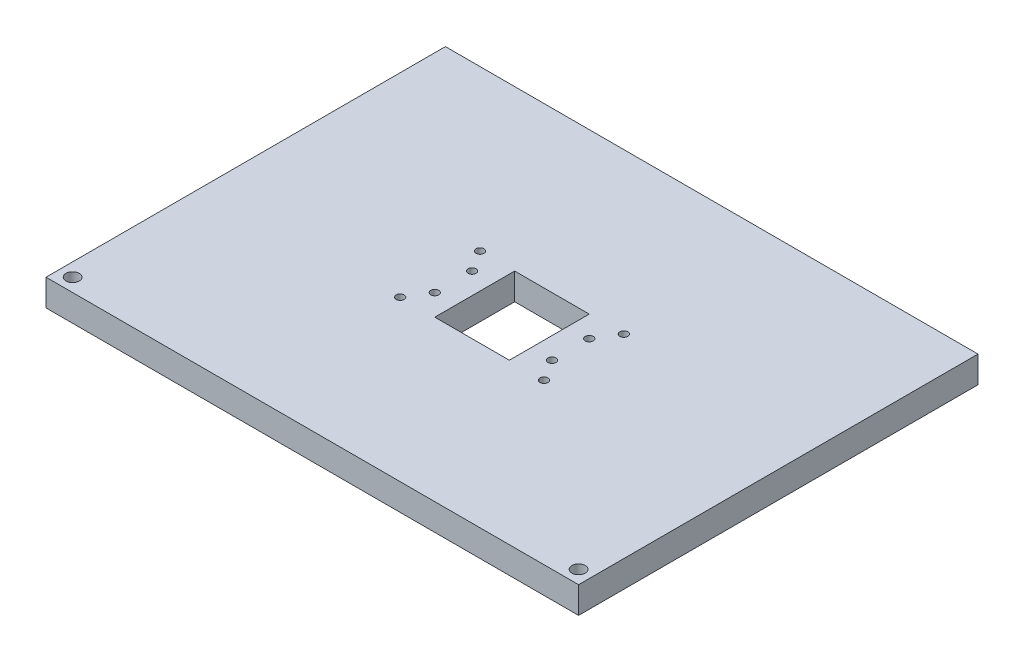
SolidWorks part; units mm, degrees
material "Perspex (TM) GS Acrylic Cast Sheet"
ref_plane "Front Plane" through (0, 0, 0) normal (0, 0, 1) x (1, 0, 0)
ref_plane "Top Plane" through (0, 0, 0) normal (0, 1, 0) x (1, 0, 0)
ref_plane "Right Plane" through (0, 0, 0) normal (1, 0, 0) x (0, 0, -1)
sketch "Sketch1" plane through (0, 0, 0) normal (0, 0, 1) x (1, 0, 0)
  line L1 (-100, 30) -> (100, 30)
  line L2 (-100, 30) -> (-100, -30)
  line L3 (-100, -30) -> (100, -30)
  line L4 (100, 30) -> (100, -30)
  line L5 (-100, 30) -> (100, -30) construction
  line L6 (-100, -30) -> (100, 30) construction
  point P0 (0, 0)
  dimension "D1" = 200
  dimension "D2" = 60
extrude "Boss-Extrude1" add sketch "Sketch1" along normal blind 10
sketch "Sketch2" plane through (0, 0, 0) normal (0, 0, -1) x (-1, 0, 0)
  line L0 (-100, -30) -> (-100, -20)
  line L1 (-100, -30) -> (-100, 30) construction
  line L2 (-100, -20) -> (100, -20)
  line L3 (100, 30) -> (100, -30) construction
  line L4 (100, -20) -> (100, -30)
  line L5 (100, -30) -> (-100, -30)
  dimension "D1" = 10
extrude "Boss-Extrude2" add sketch "Sketch2" along normal blind 140
sketch "Sketch3" plane through (0, 0, 10) normal (0, 0, 1) x (1, 0, 0)
  line L1 (0, -5.5) -> (0, 5.5) construction
  line L2 (-100, -30) -> (100, -30) construction
  circle A0 centre (0, 5) radius 15.5
  circle A1 centre (60, 5) radius 15.5
  circle A2 centre (-60, 5) radius 15.5
  dimension "D1" = 31
  dimension "D2" = 35
  dimension "D3" = 60
  dimension "D4" = 60
extrude "Cut-Extrude1" cut sketch "Sketch3" against normal blind 60
sketch "Sketch7" plane through (0, -20, 0) normal (0, 1, 0) x (1, 0, 0)
  line L0 (0, -5.5) -> (0, 5.5) construction
  line L1 (4, 80) -> (14, 80)
  line L2 (4, 80) -> (4, 50)
  line L3 (4, 50) -> (14, 50)
  line L4 (14, 80) -> (14, 50)
  line L5 (4, 80) -> (14, 50) construction
  line L6 (4, 50) -> (14, 80) construction
  line L8 (0, 115.3101) -> (0, 11.0931) construction
  line L9 (-4, 50) -> (-14, 80) construction
  line L10 (-4, 80) -> (-14, 50) construction
  line L11 (-14, 80) -> (-14, 50)
  line L12 (-4, 50) -> (-14, 50)
  line L13 (-4, 80) -> (-4, 50)
  line L14 (-4, 80) -> (-14, 80)
  line L15 (-5.5, 0) -> (5.5, 0) construction
  point P0 (9, 65)
  point P16 (-9, 65)
  dimension "D1" = 10
  dimension "D2" = 30
  dimension "D3" = 4
  dimension "D4" = 65
extrude "Cut-Extrude4" cut sketch "Sketch7" against normal blind 30
sketch "Sketch9" plane through (0, -20, 0) normal (0, 1, 0) x (1, 0, 0)
  line L0 (0, -33) -> (0, 33) construction
  line L1 (-27, 80) -> (27, 80) construction
  line L2 (-27, 80) -> (-27, 50) construction
  line L3 (-27, 50) -> (27, 50) construction
  line L4 (27, 80) -> (27, 50) construction
  line L5 (-27, 80) -> (27, 50) construction
  line L6 (-27, 50) -> (27, 80) construction
  line L7 (-33, 0) -> (33, 0) construction
  line L8 (-4, 50) -> (-4, 80) construction
  line L9 (-14, 80) -> (-14, 50) construction
  line L10 (-4, 65) -> (-14, 65) construction
  line L11 (0, 98.8977) -> (0, 27.4847) construction
  line L12 (100, -10) -> (-100, -10) construction
  line L13 (-100, -10) -> (-100, 0) construction
  line L14 (100, -10) -> (100, 0) construction
  circle A0 centre (-27, 80) radius 1.5
  circle A1 centre (27, 80) radius 1.5
  circle A2 centre (27, 50) radius 1.5
  circle A3 centre (-27, 50) radius 1.5
  circle A6 centre (-22, 72) radius 1.5
  circle A7 centre (-22, 58) radius 1.5
  circle A8 centre (22, 72) radius 1.5
  circle A9 centre (22, 58) radius 1.5
  circle A13 centre (95, -5) radius 2.5
  circle A14 centre (-95, -5) radius 2.5
  point P0 (0, 65)
  dimension "D1" = 3
  dimension "D7" = 8
  dimension "D8" = 14
  dimension "D10" = 7
  dimension "D11" = 5
  dimension "D12" = 5
  dimension "D13" = 5
  dimension "D14" = 5
  dimension "D2" = 30
  dimension "D3" = 54
  dimension "D4" = 65
extrude "Cut-Extrude6" cut sketch "Sketch9" against normal blind 20
sketch "Sketch10" plane through (0, 0, 0) normal (1, 0, 0) x (0, 0, -1)
  line L1 (0, -20) -> (-33.7656, -20)
  line L2 (0, -20) -> (0, 42.6278)
  line L3 (0, 42.6278) -> (-33.7656, 42.6278)
  line L4 (-33.7656, -20) -> (-33.7656, 42.6278)
extrude "Cut-Extrude7" cut sketch "Sketch10" against normal mid plane 260
sketch "Sketch11" plane through (0, -20, 0) normal (0, 1, 0) x (1, 0, 0)
  line L1 (-4, 80) -> (4, 80)
  line L2 (-4, 80) -> (-4, 50)
  line L3 (-4, 50) -> (4, 50)
  line L4 (4, 80) -> (4, 50)
extrude "Cut-Extrude8" cut sketch "Sketch11" against normal blind 30
